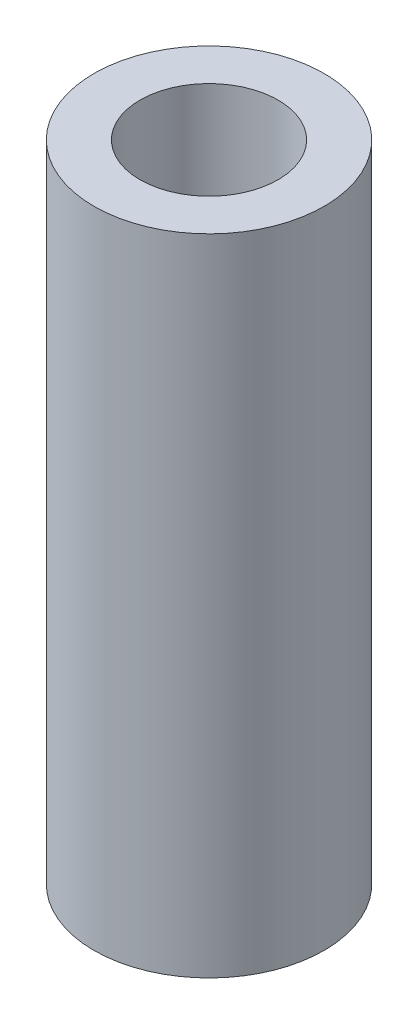
SolidWorks part; units mm, degrees
material "6061 Alloy"
ref_plane "Front Plane" through (0, 0, 0) normal (0, 0, 1) x (1, 0, 0)
ref_plane "Top Plane" through (0, 0, 0) normal (0, 1, 0) x (1, 0, 0)
ref_plane "Right Plane" through (0, 0, 0) normal (1, 0, 0) x (0, 0, -1)
sketch "Sketch1" plane through (0, 0, 0) normal (0, 1, 0) x (1, 0, 0)
  circle A0 centre (0, 0) radius 5
  circle A1 centre (0, 0) radius 1.5875
  dimension "D1" = 10
  dimension "D2" = 3.175
extrude "Boss-Extrude1" add sketch "Sketch1" along normal mid plane 28
sketch "Sketch2" plane through (0, 14, 0) normal (0, 1, 0) x (1, 0, 0)
  circle A0 centre (0, 0) radius 3
  dimension "D1" = 6
extrude "Cut-Extrude1" cut sketch "Sketch2" against normal blind 12
